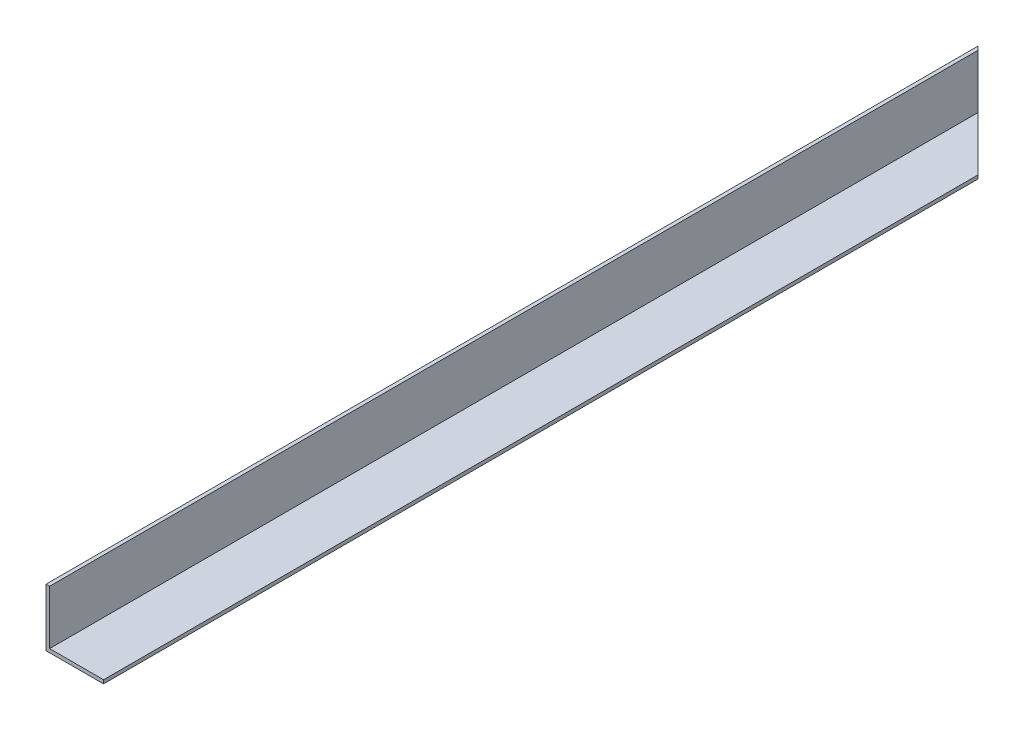
SolidWorks part; units mm, degrees
ref_plane "Front Plane" through (0, 0, 0) normal (0, 0, 1) x (1, 0, 0)
ref_plane "Top Plane" through (0, 0, 0) normal (0, 1, 0) x (1, 0, 0)
ref_plane "Right Plane" through (0, 0, 0) normal (1, 0, 0) x (0, 0, -1)
sketch "Sketch1" plane through (0, 0, 0) normal (0, 0, 1) x (1, 0, 0)
  line L0 (0, 0) -> (0, 15)
  line L1 (0, 0) -> (15, 0)
extrude "Extrude-Thin1" add sketch "Sketch1" along normal blind 259 thin thin type one direction wall 1
sketch "Sketch2" plane through (0, -1, 0) normal (0, -1, 0) x (-1, 0, 0)
  line L4 (-15, -128.5) -> (-298.4003, -128.5) construction
  line L5 (-15, 0) -> (1, 0)
  line L6 (-15, -16) -> (-15, 0)
  line L7 (1, 0) -> (-15, -16)
extrude "Cut-Extrude1" cut sketch "Sketch2" against normal through all
